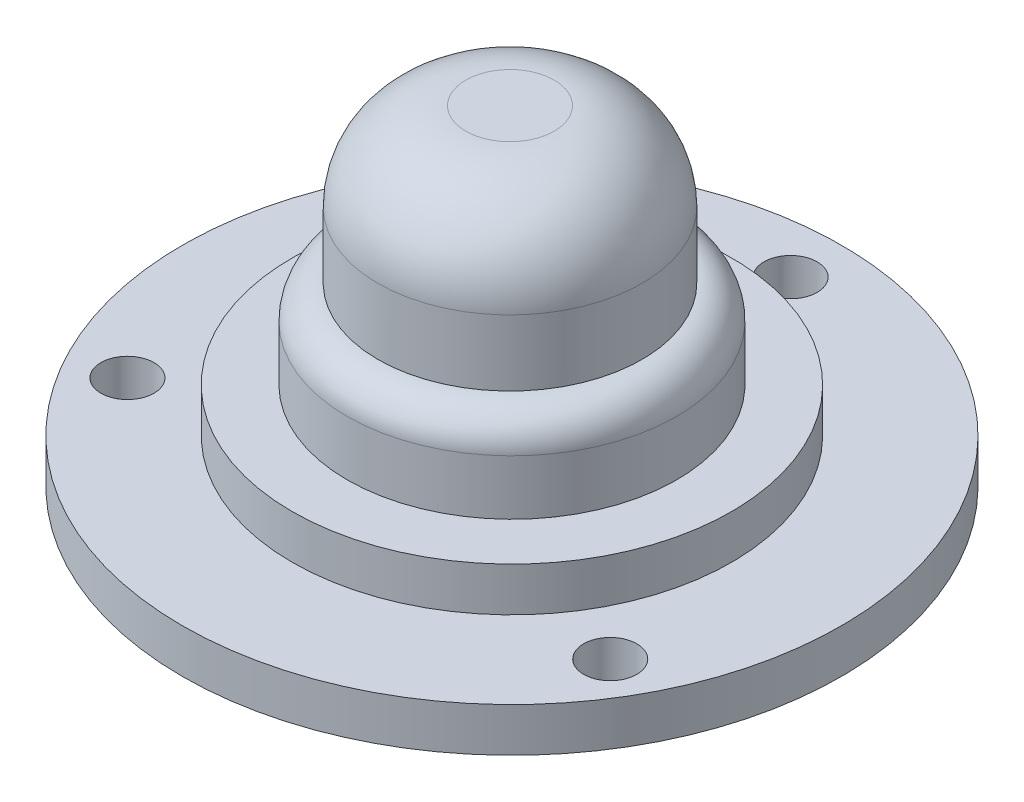
SolidWorks part; units mm, degrees
ref_plane "Front Plane" through (0, 0, 0) normal (0, 0, 1) x (1, 0, 0)
ref_plane "Top Plane" through (0, 0, 0) normal (0, 1, 0) x (1, 0, 0)
ref_plane "Right Plane" through (0, 0, 0) normal (1, 0, 0) x (0, 0, -1)
sketch "Sketch1" plane through (0, 0, 0) normal (0, 1, 0) x (1, 0, 0)
  circle A0 centre (-0.7719, 1.3286) radius 1.5
  dimension "D1" = 3
extrude "Boss-Extrude1" add sketch "Sketch1" along normal blind 0.2
sketch "Sketch2" plane through (0, 0.2, 0) normal (0, 1, 0) x (1, 0, 0)
  circle A0 centre (-0.7719, 1.3286) radius 1
  circle A1 centre (-0.7719, 1.3286) radius 1.5 construction
  dimension "D1" = 2
  dimension "D2" = 0
extrude "Boss-Extrude2" add sketch "Sketch2" along normal blind 0.2
sketch "Sketch3" plane through (0, 0.4, 0) normal (0, 1, 0) x (1, 0, 0)
  circle A0 centre (-0.7719, 1.3286) radius 0.75
  circle A1 centre (-0.7719, 1.3286) radius 1 construction
  dimension "D1" = 0
  dimension "D2" = 1.5
extrude "Boss-Extrude3" add sketch "Sketch3" along normal blind 0.4
fillet "Fillet1" radius 0.15 1 edges at (-0.7719, 0.8, -0.5786)
sketch "Sketch7" plane through (0, 0.8, 0) normal (0, 1, 0) x (1, 0, 0)
  circle A0 centre (-0.7765, 1.3244) radius 0.6013
extrude "Boss-Extrude4" add sketch "Sketch7" along normal blind 0.7
fillet "Fillet2" radius 0.4 1 edges at (-0.7765, 1.5, -0.7231)
sketch "Sketch8" plane through (0, 0.2, 0) normal (0, 1, 0) x (1, 0, 0)
  circle A0 centre (-0.7621, 2.5871) radius 0.1208
  circle A1 centre (0.3331, 0.671) radius 0.1208
  circle A2 centre (-1.8738, 0.6806) radius 0.1208
  point P9 (-0.7676, 1.3129)
  dimension "D1" = 3
extrude "Cut-Extrude1" cut sketch "Sketch8" against normal blind 0.7
